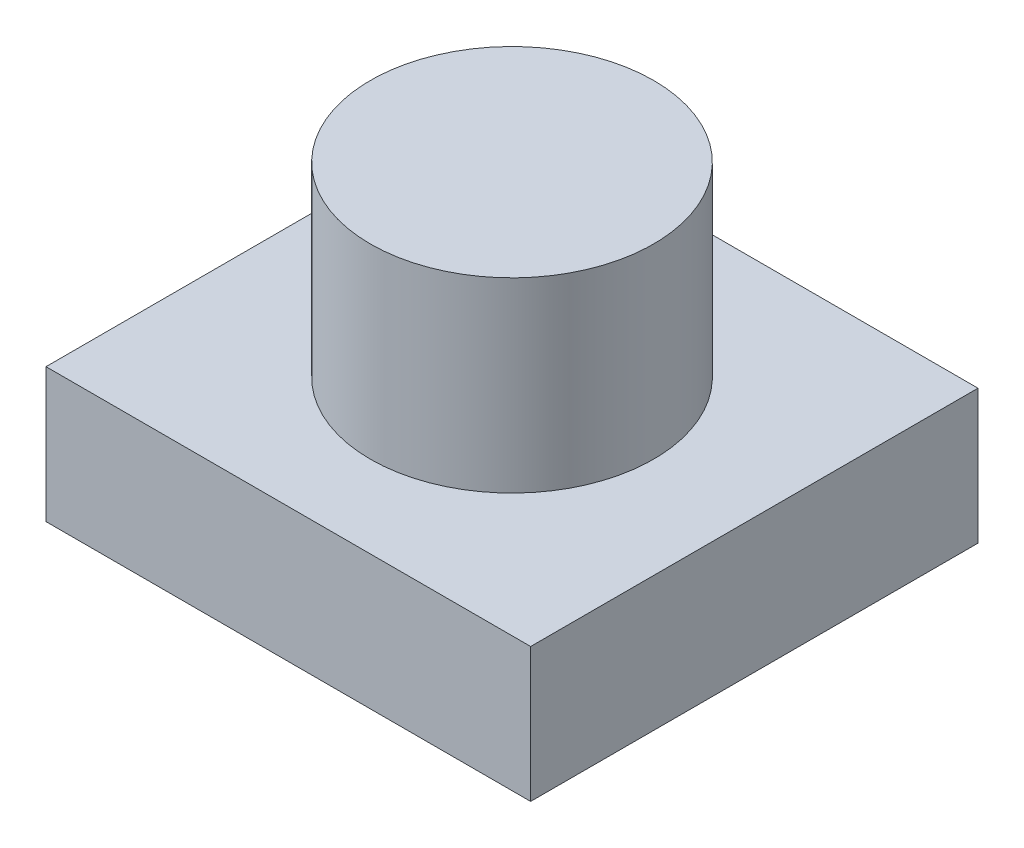
SolidWorks part; units mm, degrees
ref_plane "Front Plane" through (0, 0, 0) normal (0, 0, 1) x (1, 0, 0)
ref_plane "Top Plane" through (0, 0, 0) normal (0, 1, 0) x (1, 0, 0)
ref_plane "Right Plane" through (0, 0, 0) normal (1, 0, 0) x (0, 0, -1)
sketch "Sketch1" plane through (0, 0, 0) normal (0, 1, 0) x (1, 0, 0)
  line L1 (0, 0) -> (6.5, 0)
  line L2 (0, 0) -> (0, 6)
  line L3 (0, 6) -> (6.5, 6)
  line L4 (6.5, 0) -> (6.5, 6)
  dimension "D1" = 6
  dimension "D2" = 6.5
extrude "Boss-Extrude1" add sketch "Sketch1" along normal blind 1.8
sketch "Sketch2" plane through (0, 1.8, 0) normal (0, 1, 0) x (1, 0, 0)
  line L0 (3.25, 6) -> (3.25, 0) construction
  line L1 (6.5, 6) -> (0, 6) construction
  line L2 (0, 0) -> (6.5, 0) construction
  circle A0 centre (3.25, 3) radius 1.9
  point P6 (3.25, 3)
  dimension "D1" = 3.8
extrude "Boss-Extrude2" add sketch "Sketch2" along normal blind 2.5
